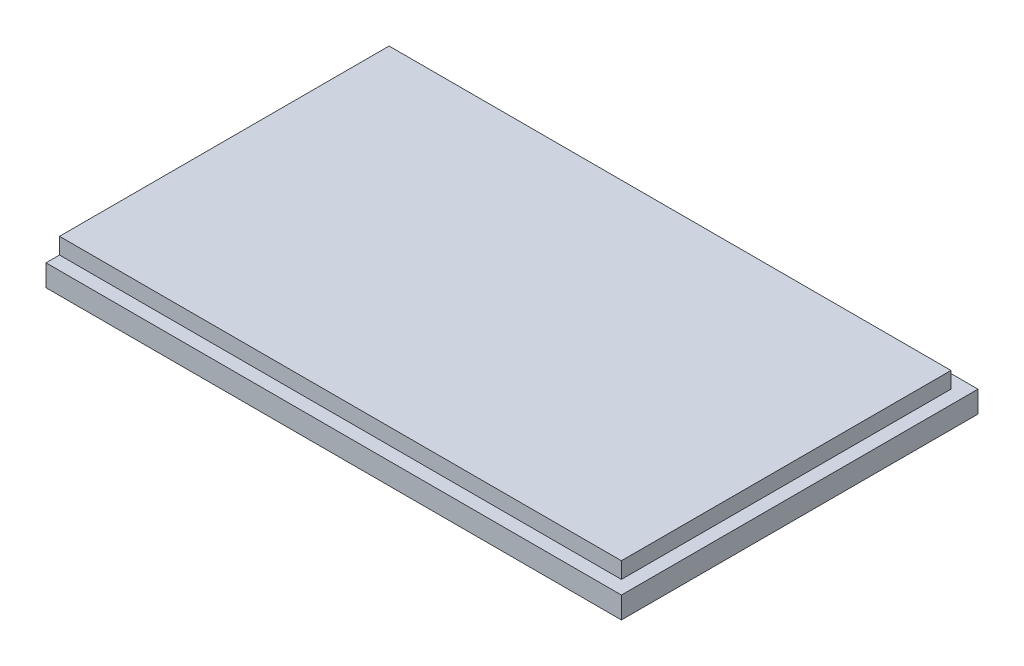
SolidWorks part; units mm, degrees
ref_plane "前视基准面" through (0, 0, 0) normal (0, 0, 1) x (1, 0, 0)
ref_plane "上视基准面" through (0, 0, 0) normal (0, 1, 0) x (1, 0, 0)
ref_plane "右视基准面" through (0, 0, 0) normal (1, 0, 0) x (0, 0, -1)
sketch "草图2" plane through (0, 0, 0) normal (0, 1, 0) x (1, 0, 0)
  line L1 (-21.3, 13.2) -> (21.3, 13.2)
  line L2 (-21.3, 13.2) -> (-21.3, -13.2)
  line L3 (-21.3, -13.2) -> (21.3, -13.2)
  line L4 (21.3, 13.2) -> (21.3, -13.2)
  line L5 (-21.3, 13.2) -> (21.3, -13.2) construction
  line L6 (-21.3, -13.2) -> (21.3, 13.2) construction
  point P0 (0, 0)
  dimension "D1" = 42.6
  dimension "D2" = 26.4
extrude "凸台-拉伸1" add sketch "草图2" along normal blind 1.6
sketch "草图3" plane through (0, 1.6, 0) normal (0, 1, 0) x (1, 0, 0)
  line L0 (-21.3, 13.2) -> (-21.3, -13.2) construction
  line L1 (-21.3, 12.2) -> (20.3, 12.2)
  line L2 (-21.3, 12.2) -> (-21.3, -12.2)
  line L3 (-21.3, -12.2) -> (20.3, -12.2)
  line L4 (20.3, 12.2) -> (20.3, -12.2)
  line L5 (21.3, 13.2) -> (-21.3, 13.2) construction
  line L6 (-21.3, -13.2) -> (21.3, -13.2) construction
  line L7 (21.3, -13.2) -> (21.3, 13.2) construction
  dimension "D1" = 1
  dimension "D2" = 1
  dimension "D3" = 1
extrude "凸台-拉伸2" add sketch "草图3" along normal blind 1.2
